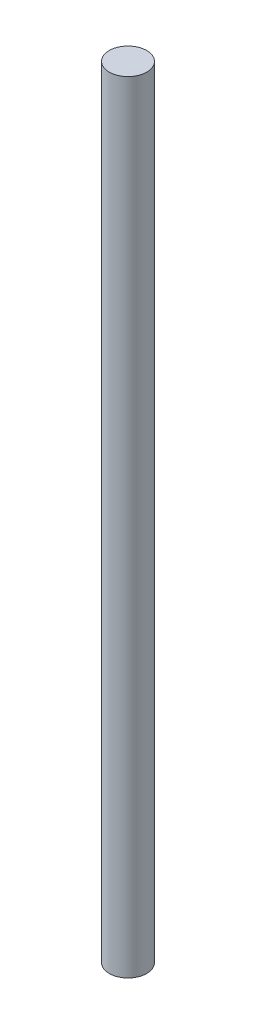
SolidWorks part; units mm, degrees
ref_plane "Front Plane" through (0, 0, 0) normal (0, 0, 1) x (1, 0, 0)
ref_plane "Top Plane" through (0, 0, 0) normal (0, 1, 0) x (1, 0, 0)
ref_plane "Right Plane" through (0, 0, 0) normal (1, 0, 0) x (0, 0, -1)
sketch "Sketch1" plane through (0, 0, 0) normal (0, 1, 0) x (1, 0, 0)
  circle A0 centre (0, 0) radius 3
  dimension "D1" = 6
extrude "Boss-Extrude1" add sketch "Sketch1" along normal blind 125
